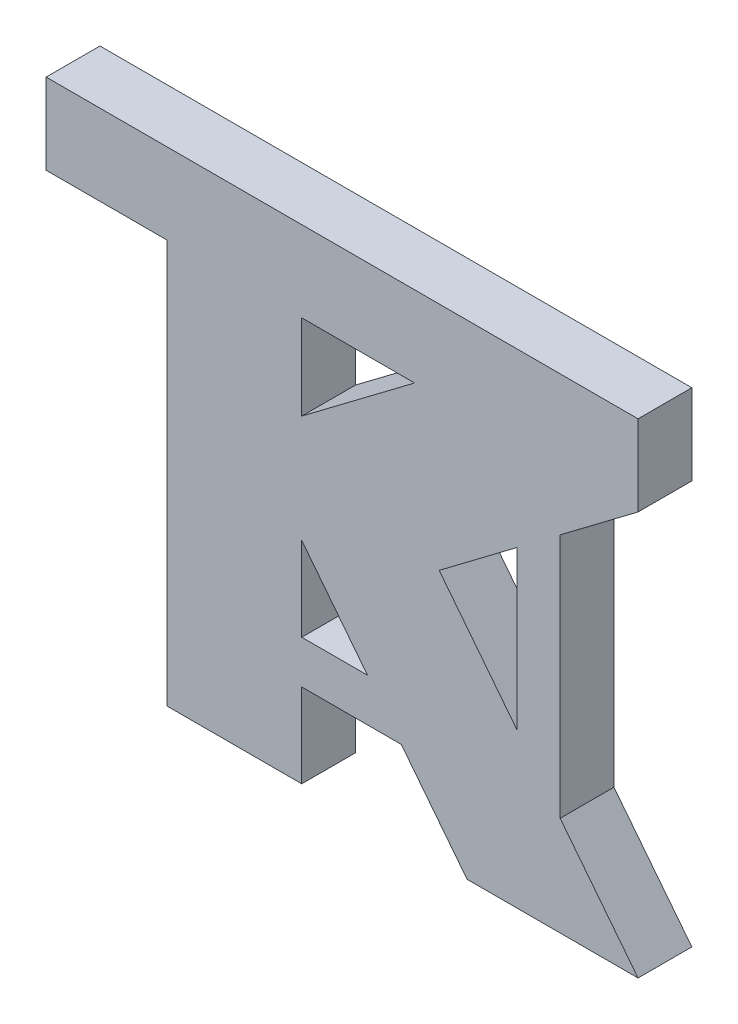
SolidWorks part; units mm, degrees
ref_plane "Front" through (0, 0, 0) normal (0, 0, 1) x (1, 0, 0)
ref_plane "Top" through (0, 0, 0) normal (0, 1, 0) x (1, 0, 0)
ref_plane "Right" through (0, 0, 0) normal (1, 0, 0) x (0, 0, -1)
sketch "Sketch1" plane through (0, 0, 0) normal (0, 0, 1) x (1, 0, 0)
  line L0 (0, 0) -> (0, 75)
  line L1 (0, 75) -> (-22.5, 75)
  line L2 (-22.5, 75) -> (-22.5, 90)
  line L5 (87.5, 75) -> (50.5389, 47.1307)
  line L6 (50.5389, 47.1307) -> (87.5, 0)
  line L7 (87.5, 0) -> (55.7293, 0)
  line L8 (55.7293, 0) -> (25, 39.1842)
  line L9 (25, 39.1842) -> (25, 0)
  line L10 (25, 0) -> (0, 0)
  line L11 (87.5, 75) -> (87.5, 90)
  line L12 (87.5, 90) -> (-22.5, 90)
  line L13 (25, 75) -> (45.9753, 75)
  line L14 (45.9753, 75) -> (25, 59.1842)
  line L15 (25, 59.1842) -> (25, 75)
  line L16 (35.4877, 67.0921) -> (50.5389, 47.1307) construction
  line L17 (59.5821, 35.5993) -> (39.91, 20.1719) construction
  line L18 (69.0195, 23.5653) -> (69.0195, 61.0653) construction
  line L19 (25, 23.5921) -> (37.2277, 23.5921)
  line L20 (25, 15.5921) -> (43.5015, 15.5921)
  line L21 (25, 19.5921) -> (40.3646, 19.5921) construction
  line L22 (32.6823, 23.5921) -> (32.6823, 15.5921) construction
  line L23 (65.0195, 42.3153) -> (73.0195, 42.3153) construction
  line L24 (65.0195, 58.0493) -> (65.0195, 28.6659)
  line L25 (73.0195, 18.4648) -> (73.0195, 64.0814)
  point P29 (12.5, 0)
  point P30 (32.6823, 19.5921)
  point P33 (69.0195, 42.3153)
  point P37 (0, 0)
  point P38 (0, 0)
  point P39 (25, 45.7422)
  point P40 (87.5, 84.854)
  dimension "D1" = 25
  dimension "D2" = 75
  dimension "D3" = 35
  dimension "D4" = 90
  dimension "D5" = 8
  dimension "D6" = 8
  dimension "D7" = 20
  dimension "D8" = 15
extrude "Boss-Extrude1" add sketch "Sketch1" along normal blind 10 contours L11 L12 L2 L1 L0 L10 L9 L8 L7 L6 L5 L14 L15 L13 | L9 L20 L8 L19 | L6 L25 L5 L24
